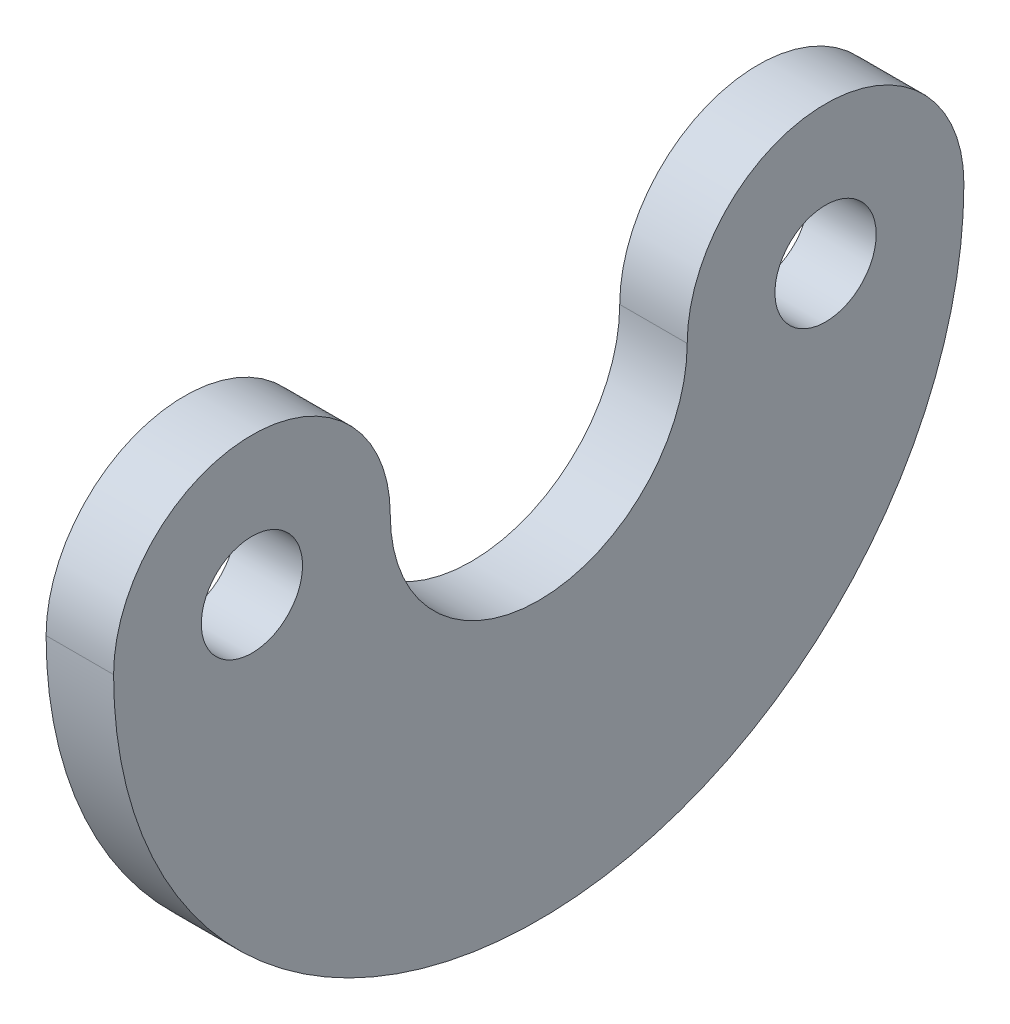
SolidWorks part; units mm, degrees
material "1060 Alloy"
ref_plane "Front Plane" through (0, 0, 0) normal (0, 0, 1) x (1, 0, 0)
ref_plane "Top Plane" through (0, 0, 0) normal (0, 1, 0) x (1, 0, 0)
ref_plane "Right Plane" through (0, 0, 0) normal (1, 0, 0) x (0, 0, -1)
sketch "Sketch1" plane through (0, 0, 0) normal (1, 0, 0) x (0, 0, -1)
  arc A0 (-4.4, 0) -> (4.4, 0) centre (0, 0) ccw
  arc A1 (-4.4, 0) -> (-12.6, 0) centre (-8.5, 0) ccw
  arc A2 (4.4, 0) -> (12.6, 0) centre (8.5, 0) cw
  arc A3 (-12.6, 0) -> (12.6, 0) centre (0, 0) ccw
  circle A4 centre (-8.5, 0) radius 1.5
  circle A5 centre (8.5, 0) radius 1.5
  dimension "D1" = 12.6
  dimension "D2" = 4.4
  dimension "D3" = 3
extrude "Boss-Extrude1" add sketch "Sketch1" along normal blind 2
